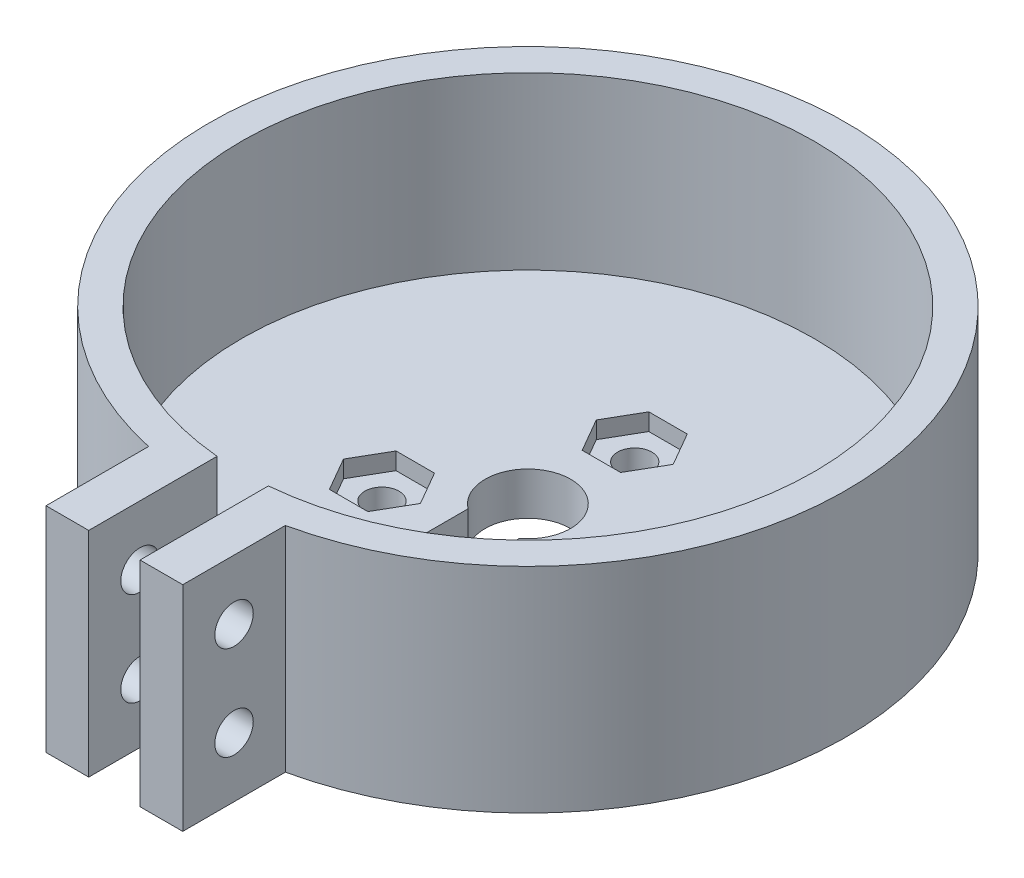
SolidWorks part; units mm, degrees
ref_plane "Спереди" through (0, 0, 0) normal (0, 0, 1) x (1, 0, 0)
ref_plane "Сверху" through (0, 0, 0) normal (0, 1, 0) x (1, 0, 0)
ref_plane "Справа" through (0, 0, 0) normal (1, 0, 0) x (0, 0, -1)
sketch "Эскиз1" plane through (0, 0, 0) normal (0, 1, 0) x (1, 0, 0)
  line L0 (0, 0) -> (0, -43.0119) construction
  circle A0 centre (0, 0) radius 37.25
  circle A1 centre (0, 0) radius 33.5
  dimension "D1" = 67
  dimension "D2" = 74.5
extrude "main" add sketch "Эскиз1" along normal blind 25
sketch "Эскиз3" plane through (0, 0, 0) normal (0, 1, 0) x (1, 0, 0)
  circle A0 centre (0, 0) radius 33.5
  circle A1 centre (0, 0) radius 5
  circle A3 centre (0, 0) radius 33.5 construction
  dimension "D1" = 10
extrude "stop" add sketch "Эскиз3" along normal blind 5
sketch "Эскиз4" plane through (0, 0, 0) normal (0, 1, 0) x (1, 0, 0)
  line L2 (0, 0) -> (0, 39.0687) construction
  line L3 (-8, -36.3808) -> (-8, -48.3808)
  line L4 (-8, -48.3808) -> (8, -48.3808)
  line L5 (8, -48.3808) -> (8, -36.3808)
  arc A0 (-8, -36.3808) -> (8, -36.3808) centre (0, 0) ccw
  circle A2 centre (0, 0) radius 37.25 construction
  point P5 (0, -48.3808)
  dimension "D1" = 12
  dimension "D2" = 8
extrude "lock" add sketch "Эскиз4" along direction (0, -1, 0) on the side of the normal up to surface (25 mm away)
sketch "Эскиз5" plane through (0, 0, 0) normal (0, 1, 0) x (1, 0, 0)
  line L0 (8, -48.3808) -> (-8, -48.3808) construction
  line L1 (-3, 0) -> (3, 0)
  line L2 (-3, 0) -> (-3, -48.3808)
  line L3 (-3, -48.3808) -> (3, -48.3808)
  line L4 (3, 0) -> (3, -48.3808)
  dimension "D1" = 3
extrude "slot" cut sketch "Эскиз5" against normal up to surface (25 mm away)
sketch "Эскиз6" plane through (8, 0, 0) normal (1, 0, 0) x (0, 0, -1)
  line L0 (-42.3808, 57.5457) -> (-42.3808, 15.5405) construction
  line L1 (-48.3808, 25) -> (-36.3808, 25) construction
  line L2 (-36.3808, 0) -> (-48.3808, 0) construction
  line L4 (-48.3808, 25) -> (-36.3808, 25) construction
  circle A0 centre (-42.3808, 7) radius 2.25
  circle A1 centre (-42.3808, 18) radius 2.25
  point P4 (-42.3808, 25)
  dimension "D1" = 7
  dimension "D2" = 4.5
  dimension "D3" = 7
extrude "small holes" cut sketch "Эскиз6" against normal through all
sketch "Эскиз7" plane through (0, 5, 0) normal (0, 1, 0) x (1, 0, 0)
  line L0 (0, 12.5) -> (0, -12.5) construction
  line L1 (0, 0) -> (10.8253, -6.25) construction
  circle A0 centre (0, 12.5) radius 2
  circle A1 centre (-10.8253, -6.25) radius 2
  circle A2 centre (0, 0) radius 12.5 construction
  circle A3 centre (10.8253, -6.25) radius 2
  dimension "D1" = 4
  dimension "D3" = 25
  dimension "D2" = 120
extrude "holes for bolts" cut sketch "Эскиз7" against normal up to next
sketch "Эскиз8" plane through (0, 5, 0) normal (0, 1, 0) x (1, 0, 0)
  line L1 (-8.5753, -10.1471) -> (-6.3253, -6.25)
  line L2 (-6.3253, -6.25) -> (-8.5753, -2.3529)
  line L3 (-8.5753, -2.3529) -> (-13.0753, -2.3529)
  line L4 (-13.0753, -2.3529) -> (-15.3253, -6.25)
  line L5 (-15.3253, -6.25) -> (-13.0753, -10.1471)
  line L6 (-13.0753, -10.1471) -> (-8.5753, -10.1471)
  line L7 (13.0753, -10.1471) -> (15.3253, -6.25)
  line L8 (15.3253, -6.25) -> (13.0753, -2.3529)
  line L9 (13.0753, -2.3529) -> (8.5753, -2.3529)
  line L10 (8.5753, -2.3529) -> (6.3253, -6.25)
  line L11 (6.3253, -6.25) -> (8.5753, -10.1471)
  line L12 (8.5753, -10.1471) -> (13.0753, -10.1471)
  line L13 (2.25, 8.6029) -> (4.5, 12.5)
  line L14 (4.5, 12.5) -> (2.25, 16.3971)
  line L15 (2.25, 16.3971) -> (-2.25, 16.3971)
  line L16 (-2.25, 16.3971) -> (-4.5, 12.5)
  line L17 (-4.5, 12.5) -> (-2.25, 8.6029)
  line L18 (-2.25, 8.6029) -> (2.25, 8.6029)
  circle A0 centre (-10.8253, -6.25) radius 4.5 construction
  circle A1 centre (10.8253, -6.25) radius 4.5 construction
  circle A2 centre (0, 12.5) radius 4.5 construction
  dimension "D1" = 9
extrude "hexagons" cut sketch "Эскиз8" against normal blind 2
sketch "Эскиз10" plane through (-8, 0, 0) normal (-1, 0, 0) x (0, 0, 1)
  circle A0 centre (42.3808, 7) radius 6.8764
